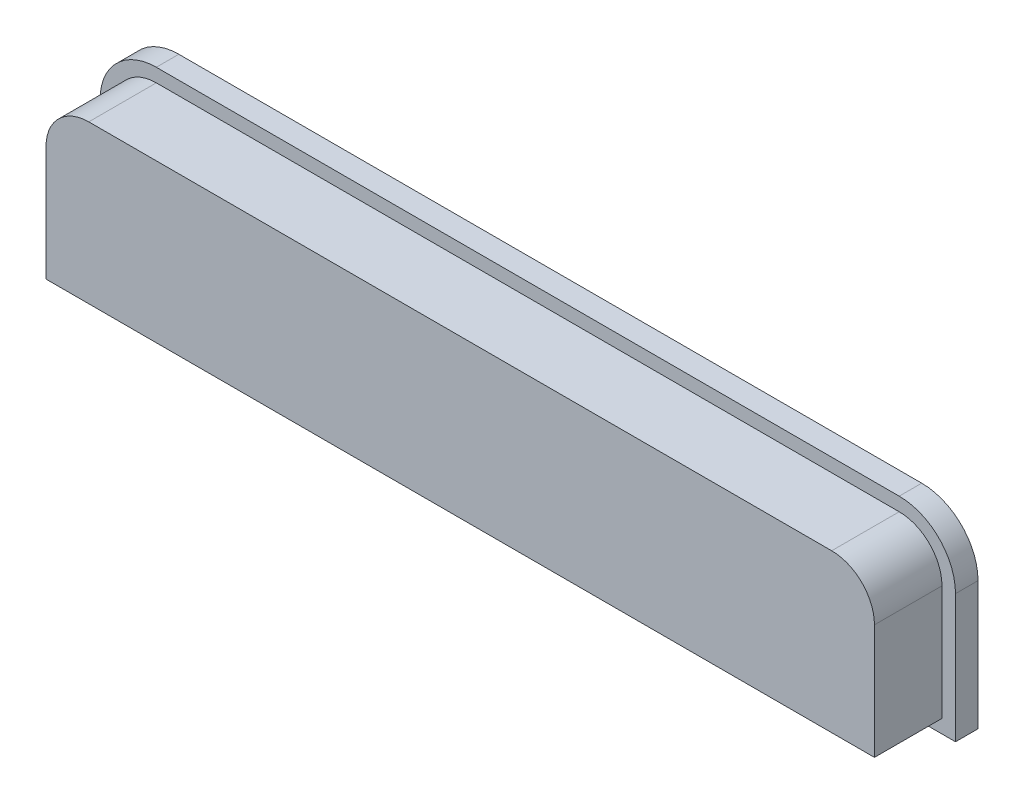
SolidWorks part; units mm, degrees
ref_plane "Front Plane" through (0, 0, 0) normal (0, 0, 1) x (1, 0, 0)
ref_plane "Top Plane" through (0, 0, 0) normal (0, 1, 0) x (1, 0, 0)
ref_plane "Right Plane" through (0, 0, 0) normal (1, 0, 0) x (0, 0, -1)
sketch "Sketch1" plane through (0, 0, 0) normal (0, 0, 1) x (1, 0, 0)
  line L0 (0, 0) -> (0, 5.7)
  line L1 (2.5, 8.2) -> (35.5, 8.2)
  line L2 (38, 5.7) -> (38, 0)
  line L3 (38, 0) -> (0, 0)
  arc A0 (0, 5.7) -> (2.5, 8.2) centre (2.5, 5.7) cw
  arc A1 (35.5, 8.2) -> (38, 5.7) centre (35.5, 5.7) cw
  dimension "D1" = 38
  dimension "D3" = 2.5
  dimension "D2" = 8.2
extrude "Boss-Extrude1" add sketch "Sketch1" along normal blind 1
sketch "Sketch2" plane through (0, 0, 1) normal (0, 0, 1) x (1, 0, 0)
  line L0 (0.6, 0.6) -> (0.6, 5.7)
  line L1 (2.5, 7.6) -> (35.5, 7.6)
  line L2 (37.4, 5.7) -> (37.4, 0.6)
  line L3 (37.4, 0.6) -> (0.6, 0.6)
  line L4 (2.5, 7.6) -> (2.5, 8.2) construction
  line L5 (0.6, 0.6) -> (0.6, 0) construction
  line L6 (0, 0) -> (38, 0) construction
  arc A0 (0.6, 5.7) -> (2.5, 7.6) centre (2.5, 5.7) cw
  arc A1 (35.5, 7.6) -> (37.4, 5.7) centre (35.5, 5.7) cw
  arc A2 (2.5, 8.2) -> (0, 5.7) centre (2.5, 5.7) ccw construction
  arc A3 (38, 5.7) -> (35.5, 8.2) centre (35.5, 5.7) ccw construction
  dimension "D1" = 0.6
extrude "Boss-Extrude2" add sketch "Sketch2" along normal blind 3
